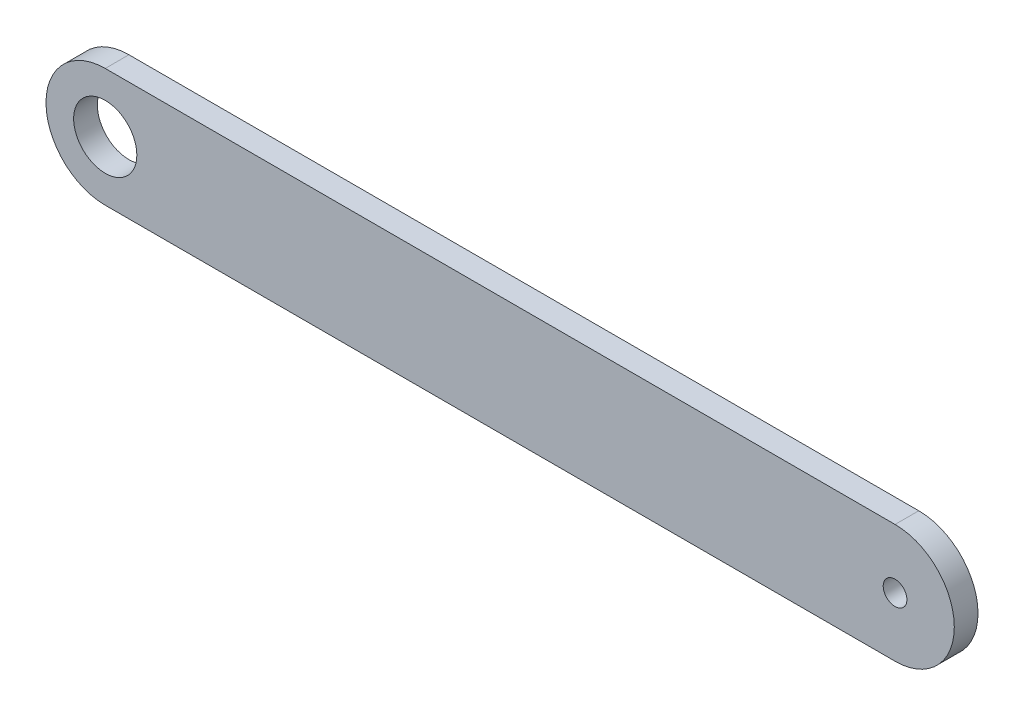
SolidWorks part; units mm, degrees
ref_plane "Front Plane" through (0, 0, 0) normal (0, 0, 1) x (1, 0, 0)
ref_plane "Top Plane" through (0, 0, 0) normal (0, 1, 0) x (1, 0, 0)
ref_plane "Right Plane" through (0, 0, 0) normal (1, 0, 0) x (0, 0, -1)
sketch "Sketch1" plane through (0, 0, 0) normal (0, 0, 1) x (1, 0, 0)
  line L0 (0, 7.5) -> (100, 7.5)
  line L1 (0, -7.5) -> (100, -7.5)
  circle A0 centre (0, 0) radius 7.5
  circle A1 centre (100, 0) radius 7.5
  dimension "D1" = 15
  dimension "D2" = 15
  dimension "D3" = 100
extrude "Boss-Extrude1" add sketch "Sketch1" along normal blind 3
sketch "Sketch2" plane through (0, 0, 3) normal (0, 0, 1) x (1, 0, 0)
  circle A0 centre (0, 0) radius 4
  circle A1 centre (100, 0) radius 1.5
  dimension "D1" = 8
  dimension "D2" = 3
extrude "Cut-Extrude1" cut sketch "Sketch2" against normal blind 10
